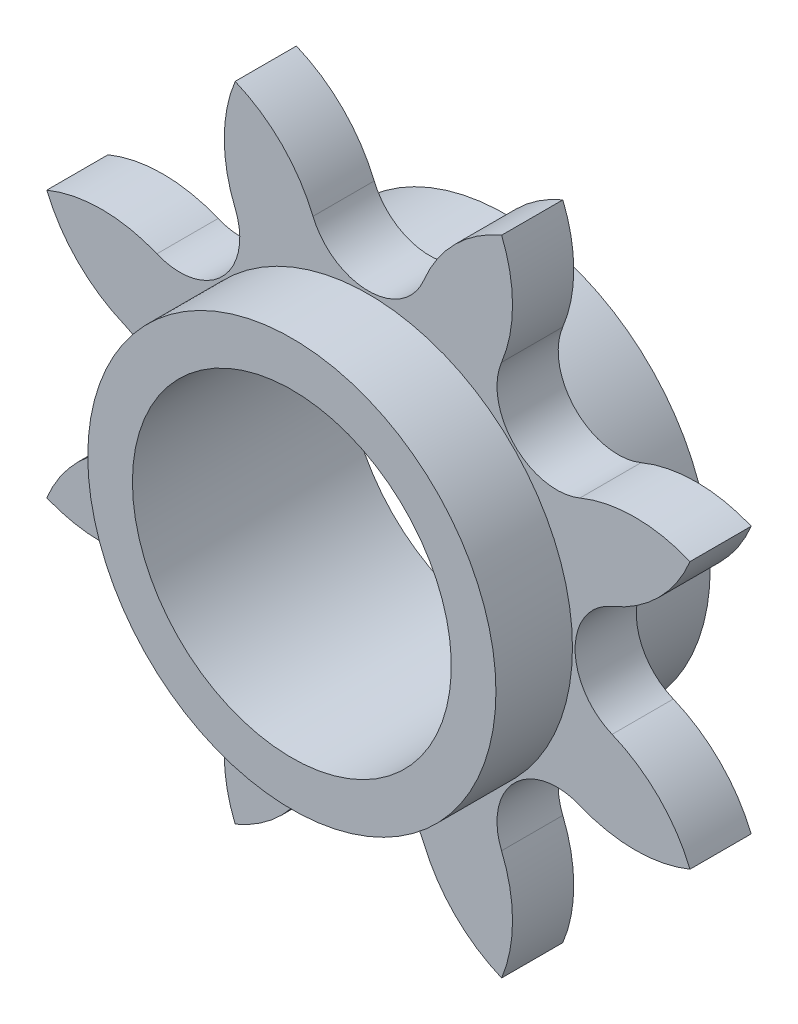
SolidWorks part; units mm, degrees
ref_plane "Front Plane" through (0, 0, 0) normal (0, 0, 1) x (1, 0, 0)
ref_plane "Top Plane" through (0, 0, 0) normal (0, 1, 0) x (1, 0, 0)
ref_plane "Right Plane" through (0, 0, 0) normal (1, 0, 0) x (0, 0, -1)
sketch "Model" plane through (0, 0, 0) normal (0, 0, 1) x (1, 0, 0)
  arc A0 (5.2199, 8.2903) -> (5.2225, 12.6083) centre (0, 10.4525) ccw
  arc A1 (5.2225, 12.6083) -> (2.1711, 9.5532) centre (7.391, 7.391) ccw
  arc A2 (-2.1711, 9.5532) -> (2.1711, 9.5532) centre (0, 10.4525) ccw
  arc A3 (-2.1711, 9.5532) -> (-5.2225, 12.6083) centre (-7.391, 7.391) ccw
  arc A4 (-5.2225, 12.6083) -> (-5.2199, 8.2903) centre (0, 10.4525) ccw
  arc A5 (-8.2903, 5.2199) -> (-5.2199, 8.2903) centre (-7.391, 7.391) ccw
  arc A6 (-8.2903, 5.2199) -> (-12.6083, 5.2225) centre (-10.4524, 0) ccw
  arc A7 (-12.6083, 5.2225) -> (-9.5532, 2.1711) centre (-7.391, 7.391) ccw
  arc A8 (-9.5532, -2.1711) -> (-9.5532, 2.1711) centre (-10.4525, 0) ccw
  arc A9 (-9.5532, -2.1711) -> (-12.6083, -5.2225) centre (-7.391, -7.391) ccw
  arc A10 (-12.6083, -5.2225) -> (-8.2903, -5.2199) centre (-10.4525, 0) ccw
  arc A11 (-5.2199, -8.2903) -> (-8.2903, -5.2199) centre (-7.391, -7.391) ccw
  arc A12 (-5.2199, -8.2903) -> (-5.2225, -12.6083) centre (0, -10.4524) ccw
  arc A13 (-5.2225, -12.6083) -> (-2.1711, -9.5532) centre (-7.391, -7.391) ccw
  arc A14 (2.1711, -9.5532) -> (-2.1711, -9.5532) centre (0, -10.4525) ccw
  arc A15 (2.1711, -9.5532) -> (5.2225, -12.6083) centre (7.391, -7.391) ccw
  arc A16 (5.2225, -12.6083) -> (5.2199, -8.2903) centre (0, -10.4525) ccw
  arc A17 (8.2903, -5.2199) -> (5.2199, -8.2903) centre (7.391, -7.391) ccw
  arc A18 (8.2903, -5.2199) -> (12.6083, -5.2225) centre (10.4524, 0) ccw
  arc A19 (12.6083, -5.2225) -> (9.5532, -2.1711) centre (7.391, -7.391) ccw
  arc A20 (9.5532, 2.1711) -> (9.5532, -2.1711) centre (10.4525, 0) ccw
  arc A21 (9.5532, 2.1711) -> (12.6083, 5.2225) centre (7.391, 7.391) ccw
  arc A22 (12.6083, 5.2225) -> (8.2903, 5.2199) centre (10.4525, 0) ccw
  arc A23 (5.2199, 8.2903) -> (8.2903, 5.2199) centre (7.391, 7.391) ccw
  circle A24 centre (0, 0) radius 6.25
extrude "Boss-Extrude1" add sketch "Model" along normal blind 2.4
sketch "Sketch2" plane through (0, 0, 0) normal (0, 0, -1) x (-1, 0, 0)
  circle A0 centre (0, 0) radius 6.25
  circle A1 centre (0, 0) radius 8
extrude "Boss-Extrude2" add sketch "Sketch2" along normal blind 3
ref_plane "Plane1" through (0, 0, 1.2) normal (0, 0, -1) x (-1, 0, 0)
mirror "Mirror1" about plane through (0, 0, 1.2) normal (0, 0, -1) of "Boss-Extrude2"
